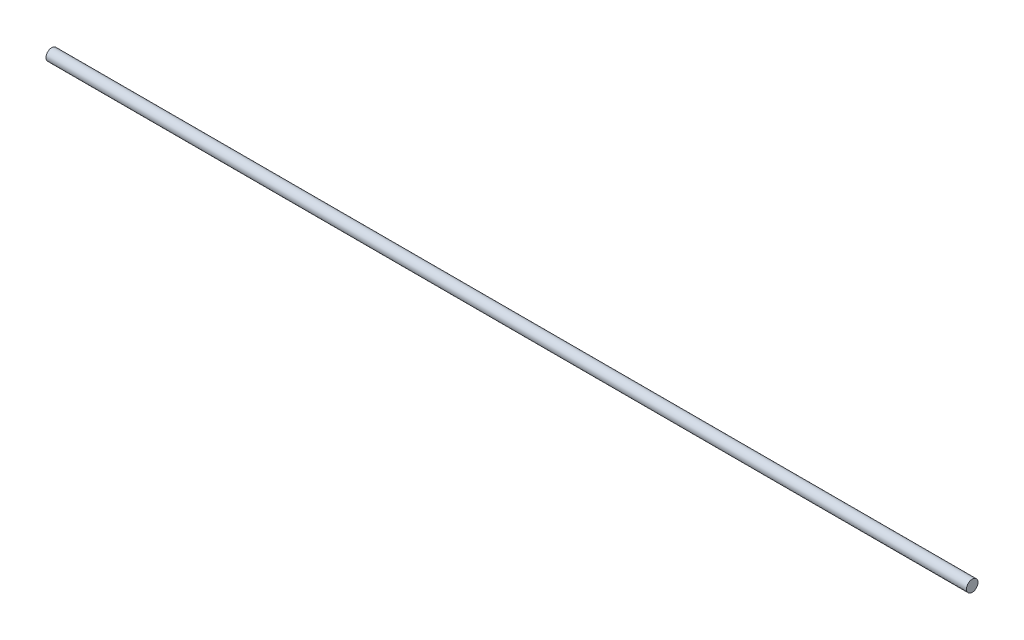
SolidWorks part; units mm, degrees
material "AISI Тип 316L нержавеющая сталь"
ref_plane "Спереди" through (0, 0, 0) normal (0, 0, 1) x (1, 0, 0)
ref_plane "Сверху" through (0, 0, 0) normal (0, 1, 0) x (1, 0, 0)
ref_plane "Справа" through (0, 0, 0) normal (1, 0, 0) x (0, 0, -1)
sketch "Эскиз1" plane through (0, 0, 0) normal (1, 0, 0) x (0, 0, -1)
  line L0 (0, 10) -> (0, -10) construction
  circle A0 centre (0, 0) radius 10
  dimension "D1" = 20
extrude "Бобышка-Вытянуть1" add sketch "Эскиз1" along normal mid plane 1600
sketch "Эскиз2" plane through (0, 0, 0) normal (0, 0, 1) x (1, 0, 0)
  line L0 (-800, 10) -> (800, 10) construction
  dimension "D1" = 1600
ref_plane "Плоскость1" through (0, 10, 0) normal (0, 1, 0) x (1, 0, 0)
